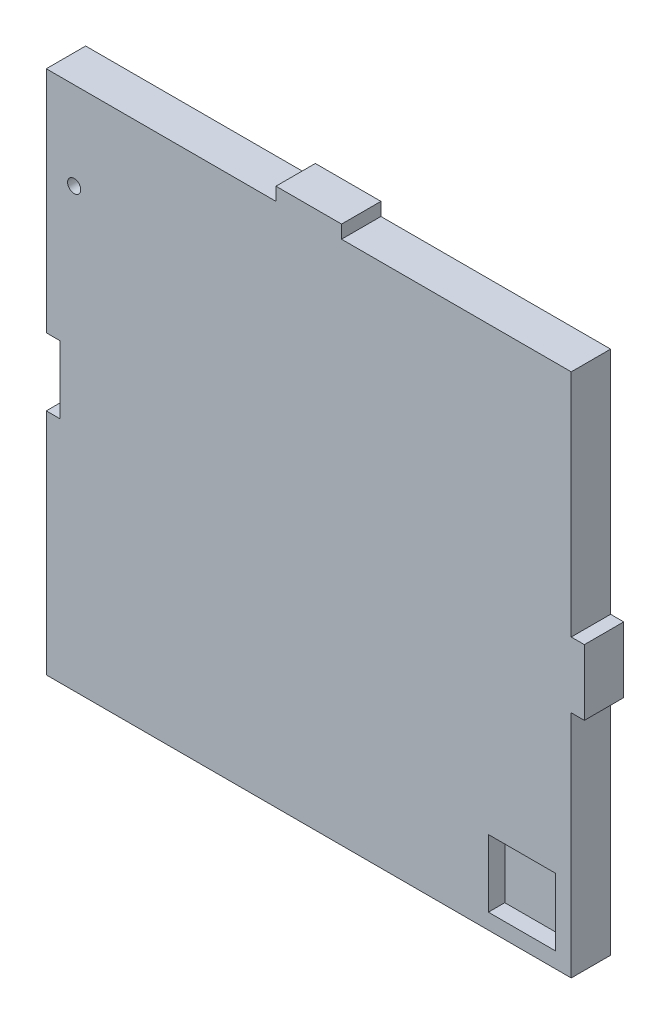
SolidWorks part; units mm, degrees
ref_plane "Front Plane" through (0, 0, 0) normal (0, 0, 1) x (1, 0, 0)
ref_plane "Top Plane" through (0, 0, 0) normal (0, 1, 0) x (1, 0, 0)
ref_plane "Right Plane" through (0, 0, 0) normal (1, 0, 0) x (0, 0, -1)
sketch "Sketch1" plane through (0, 0, 0) normal (0, 0, 1) x (1, 0, 0)
  line L0 (0, 0) -> (69.7, 0)
  line L1 (90.3, 0) -> (69.7, 0)
  line L4 (90.3, 0) -> (160, 0)
  line L5 (160, 0) -> (160, 70)
  line L6 (160, 70) -> (164, 70)
  line L7 (164, 70) -> (164, 90)
  line L8 (164, 90) -> (160, 90)
  line L9 (160, 90) -> (160, 160)
  line L10 (160, 160) -> (90, 160)
  line L11 (90, 160) -> (90, 164)
  line L12 (90, 164) -> (70, 164)
  line L13 (70, 164) -> (70, 160)
  line L14 (70, 160) -> (0, 160)
  line L15 (0, 160) -> (0, 90.3)
  line L16 (0, 90.3) -> (4.2, 90.3)
  line L17 (4.2, 90.3) -> (4.2, 69.7)
  line L18 (4.2, 69.7) -> (0, 69.7)
  line L19 (0, 69.7) -> (0, 0)
  circle A0 centre (8.5, 133.3) radius 2
  dimension "D1" = 4
extrude "Boss-Extrude1" add sketch "Sketch1" along normal blind 12
sketch "Sketch2" plane through (0, 0, 12) normal (0, 0, 1) x (1, 0, 0)
  line L0 (134.75, 4.75) -> (155.25, 4.75)
  line L1 (155.25, 4.75) -> (155.25, 25.25)
  line L2 (155.25, 25.25) -> (134.75, 25.25)
  line L3 (134.75, 25.25) -> (134.75, 4.75)
extrude "Cut-Extrude1" cut sketch "Sketch2" against normal blind 5
sketch "Sketch3" plane through (0, 0, 0) normal (0, 0, -1) x (-1, 0, 0)
  circle A0 centre (-8.5, 133.3) radius 3.45
  dimension "D1" = 6.9
extrude "Cut-Extrude2" cut sketch "Sketch3" against normal blind 8
